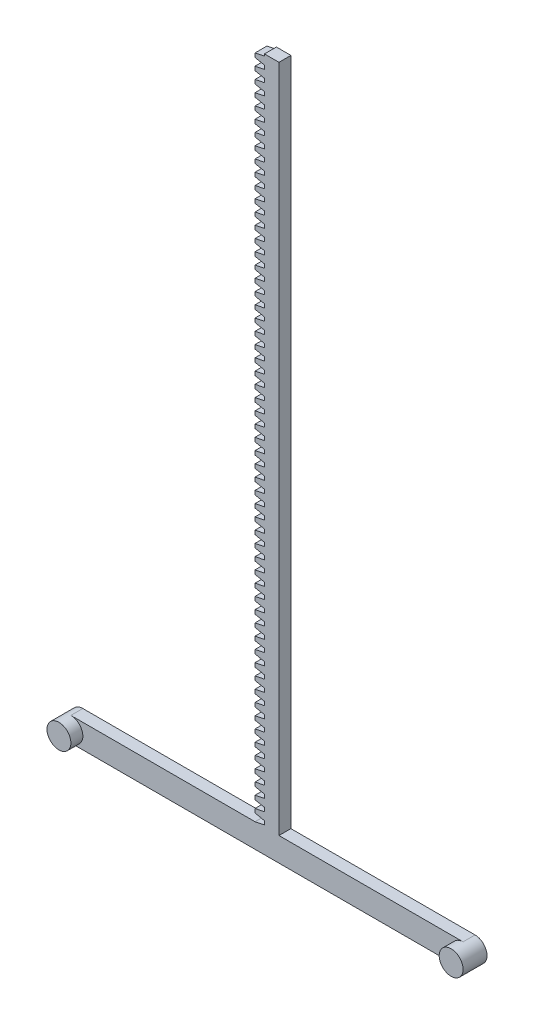
SolidWorks part; units mm, degrees
ref_plane "Front Plane" through (0, 0, 0) normal (0, 0, 1) x (1, 0, 0)
ref_plane "Top Plane" through (0, 0, 0) normal (0, 1, 0) x (1, 0, 0)
ref_plane "Right Plane" through (0, 0, 0) normal (1, 0, 0) x (0, 0, -1)
sketch "Sketch1" plane through (0, 0, 0) normal (0, 0, 1) x (1, 0, 0)
  line L0 (0, 0) -> (0, 69.9279) construction
  line L1 (-52.07, 3.6243) -> (-3.175, 3.6243)
  line L2 (3.175, 3.6243) -> (52.07, 3.6243)
  line L3 (-52.07, -2.7257) -> (52.07, -2.7257)
  line L5 (-3.175, 3.6243) -> (-3.175, 181.4243)
  line L6 (-3.175, 181.4243) -> (3.175, 181.4243)
  line L7 (3.175, 3.6243) -> (3.175, 181.4243)
  arc A0 (-52.07, 3.6243) -> (-52.07, -2.7257) centre (-52.07, 0.4493) ccw
  arc A1 (52.07, -2.7257) -> (52.07, 3.6243) centre (52.07, 0.4493) ccw
  dimension "D1" = 3.175
  dimension "D2" = 3.175
  dimension "D3" = 177.8
extrude "Boss-Extrude1" add sketch "Sketch1" along normal blind 3.175
sketch "Sketch2" plane through (0, 0, 0) normal (0, 0, 1) x (1, 0, 0)
  circle A0 centre (52.07, 0.4493) radius 3.175
  circle A1 centre (-52.07, 0.4493) radius 3.175
extrude "Boss-Extrude2" add sketch "Sketch2" along normal blind 6.35
sketch "Sketch4" plane through (0, 0, 3.175) normal (0, 0, 1) x (1, 0, 0)
  line L0 (-3.175, 4.6243) -> (0.2411, 4.6243) construction
  line L2 (-3.175, 3.6243) -> (-3.175, 5.6243)
  line L4 (-0.675, 4.1243) -> (-0.675, 5.1243)
  line L5 (-3.175, 3.6243) -> (-0.675, 4.1243)
  line L6 (-3.175, 5.6243) -> (-0.675, 5.1243)
  dimension "D1" = 2
  dimension "D3" = 0.5
  dimension "D4" = 0.5
extrude "Cut-Extrude1" cut sketch "Sketch4" against normal blind 3.175
pattern_linear "LPattern1" count 65 spacing 3.048 along (0, 1, 0) of "Cut-Extrude1"
